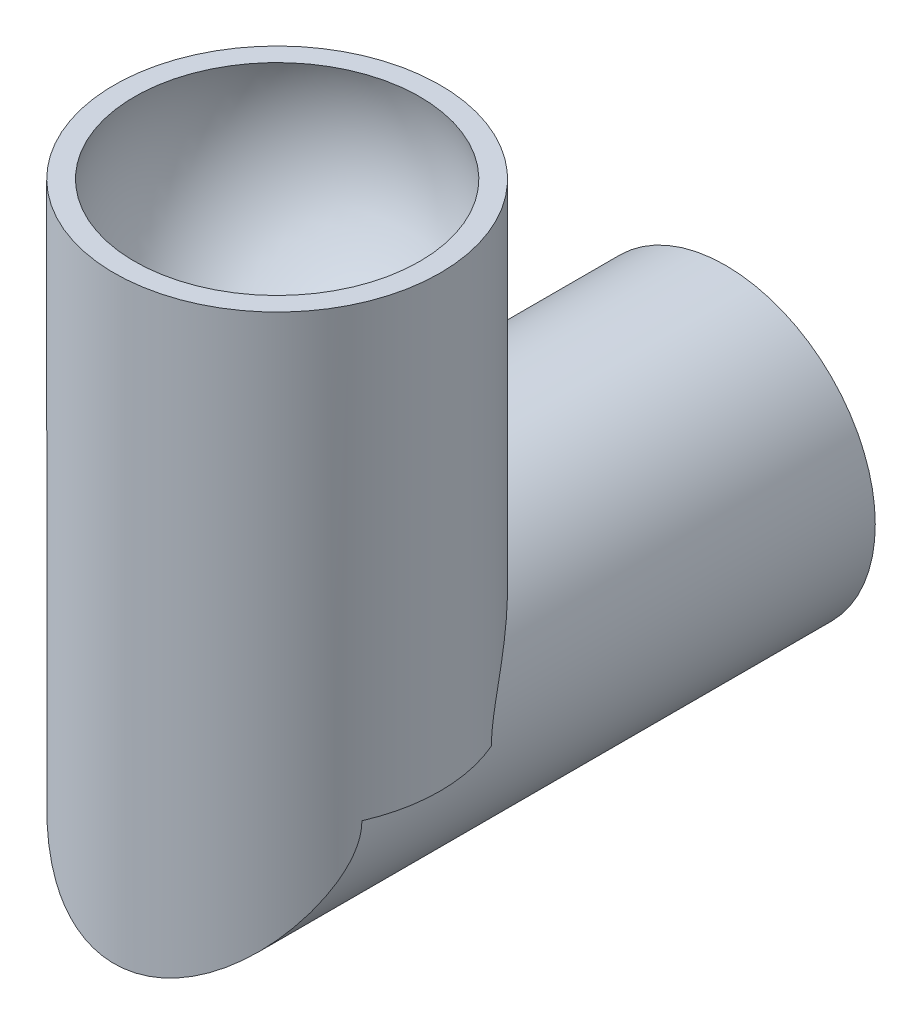
SolidWorks part; units mm, degrees
ref_plane "前视基准面" through (0, 0, 0) normal (0, 0, 1) x (1, 0, 0)
ref_plane "上视基准面" through (0, 0, 0) normal (0, 1, 0) x (1, 0, 0)
ref_plane "右视基准面" through (0, 0, 0) normal (1, 0, 0) x (0, 0, -1)
sketch "草图1" plane through (0, 0, 0) normal (0, 0, 1) x (1, 0, 0)
  line L0 (0, 0) -> (0, 6.614) construction
  line L1 (0, 6.614) -> (7.5003, 6.614) construction
  line L2 (7.5003, 6.614) -> (-7.5003, 6.614) construction
  line L3 (0, 0) -> (0, 3) construction
  line L6 (21.7945, 6) -> (21.7945, -54)
  line L7 (0, -54) -> (21.7945, -54)
  line L8 (19.0788, 6) -> (21.7945, 6)
  line L9 (0, -54) -> (0, -20)
  line L10 (0, 6.614) -> (0, -34) construction
  arc A0 (0, -20) -> (19.0788, 6) centre (0, 0) ccw
  point P8 (0, -20)
  point P9 (0, 3)
  dimension "D1" = 40
  dimension "D2" = 6.614
  dimension "D3" = 3
  dimension "D4" = 22
  dimension "D6" = 60
sketch "草图2" plane through (0, 0, 0) normal (0, 1, 0) x (1, 0, 0)
  circle A0 centre (0, 0) radius 11
sweep "扫描1" add profiles "草图1" path "草图2"
sketch "草图5" plane through (0, 0, 0) normal (0, 0, 1) x (1, 0, 0)
  line L0 (-21.7945, -54) -> (21.7945, -54) construction
  circle A0 centre (0, -54) radius 20
  dimension "D1" = 40
extrude "凸台-拉伸1" add sketch "草图5" against normal blind 60 and the other way up to surface other way up to face at (21.7945, -24, 0)
sketch "草图6" plane through (0, 0, 0) normal (1, 0, 0) x (0, 0, -1)
  line L0 (60, -54) -> (0, -54)
  line L1 (60, -74) -> (60, -34) construction
  line L2 (0, -54) -> (0, 6)
sketch "草图7" plane through (0, 0, -60) normal (0, 0, -1) x (-1, 0, 0)
  line L0 (0, -54) -> (0, 6) construction
  circle A0 centre (0, -54) radius 10
  dimension "D1" = 20
sweep "切除-扫描1" cut profiles "草图7" path "草图6"
